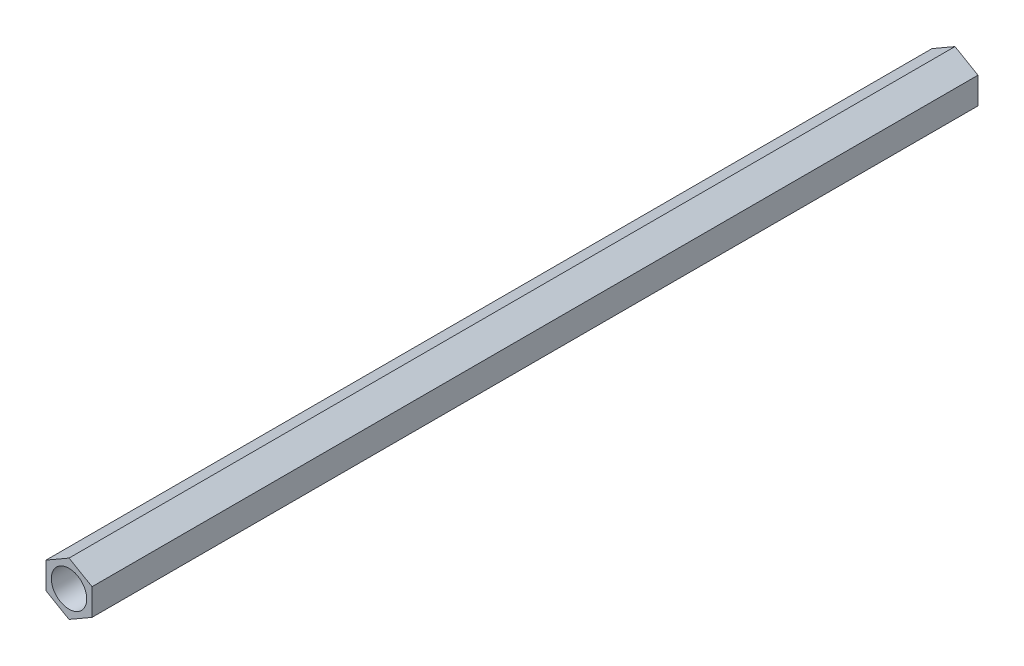
SolidWorks part; units mm, degrees
ref_plane "Front Plane" through (0, 0, 0) normal (1, 0, 0) x (0, 1, 0)
ref_plane "Top Plane" through (0, 0, 0) normal (0, 0, 1) x (0, 1, 0)
ref_plane "Right Plane" through (0, 0, 0) normal (0, 1, 0) x (-1, 0, 0)
sketch "Sketch1" plane through (0, 0, 0) normal (0, 0, 1) x (0, 1, 0)
  line L1 (3, 0) -> (1.5, 2.5981)
  line L2 (1.5, 2.5981) -> (-1.5, 2.5981)
  line L3 (-1.5, 2.5981) -> (-3, 0)
  line L4 (-3, 0) -> (-1.5, -2.5981)
  line L5 (-1.5, -2.5981) -> (1.5, -2.5981)
  line L6 (1.5, -2.5981) -> (3, 0)
  circle A0 centre (0, 0) radius 2.5981 construction
  dimension "D1" = 6
extrude "Boss-Extrude1" add sketch "Sketch1" along normal blind 100
sketch "Sketch2" plane through (0, 0, 100) normal (0, 0, 1) x (1, 0, 0)
  circle A0 centre (0, 0) radius 2
  dimension "D1" = 4
extrude "Cut-Extrude1" cut sketch "Sketch2" against normal blind 120
